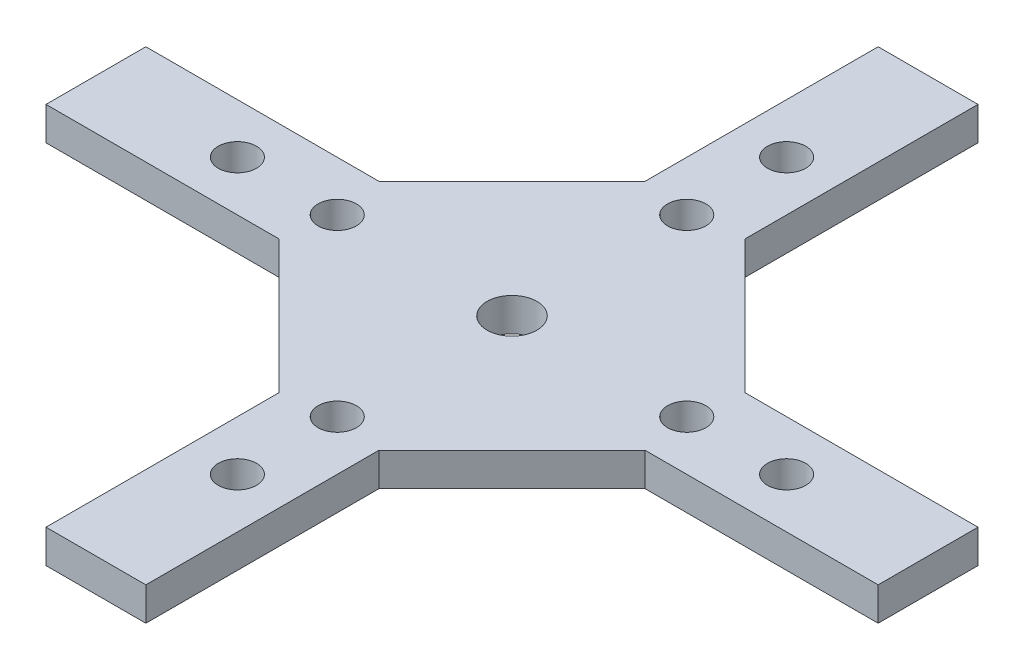
SolidWorks part; units mm, degrees
ref_plane "前视基准面" through (0, 0, 0) normal (0, 0, 1) x (1, 0, 0)
ref_plane "上视基准面" through (0, 0, 0) normal (0, 1, 0) x (1, 0, 0)
ref_plane "右视基准面" through (0, 0, 0) normal (1, 0, 0) x (0, 0, -1)
sketch "草图1" plane through (0, 0, 0) normal (0, 1, 0) x (1, 0, 0)
  line L1 (-25, -3) -> (25, -3)
  line L2 (-25, -3) -> (-25, 3)
  line L3 (-25, 3) -> (25, 3)
  line L4 (25, -3) -> (25, 3)
  line L5 (-25, -3) -> (25, 3) construction
  line L6 (-25, 3) -> (25, -3) construction
  line L7 (-3, -25) -> (3, -25)
  line L8 (-3, -25) -> (-3, 25)
  line L9 (-3, 25) -> (3, 25)
  line L10 (3, -25) -> (3, 25)
  line L11 (-3, -25) -> (3, 25) construction
  line L12 (-3, 25) -> (3, -25) construction
  circle A0 centre (0, 0) radius 1.5
  dimension "D1" = 3
  dimension "D2" = 50
  dimension "D3" = 6
  dimension "D4" = 6
  dimension "D5" = 50
extrude "凸台-拉伸1" add sketch "草图1" along normal blind 2 contours L1 L8 L3 L2 | L10 L1 L4 L3 | L3 L10 L9 L8 | L7 L10 L1 L8 | L1 L10 L3 L8 A0
sketch "草图2" plane through (0, 2, 0) normal (0, 1, 0) x (1, 0, 0)
  circle A0 centre (0, 10.5) radius 1.15
  circle A1 centre (0, 0) radius 1.5 construction
  circle A2 centre (0, 16.5) radius 1.15
  circle A3 centre (16.5, 0) radius 1.15
  circle A4 centre (10.5, 0) radius 1.15
  circle A5 centre (0, -16.5) radius 1.15
  circle A6 centre (0, -10.5) radius 1.15
  circle A7 centre (-16.5, 0) radius 1.15
  circle A8 centre (-10.5, 0) radius 1.15
  point P21 (0, 0)
  dimension "D1" = 10.5
  dimension "D2" = 16.5
  dimension "D3" = 2.3
  dimension "D4" = 2.3
  dimension "D5" = 4
extrude "切除-拉伸1" cut sketch "草图2" against normal blind 12
chamfer "倒角1" distance 8 angle 45 4 edges at (3, 1, 3) (-3, 1, 3) (3, 1, -3) (-3, 1, -3)
